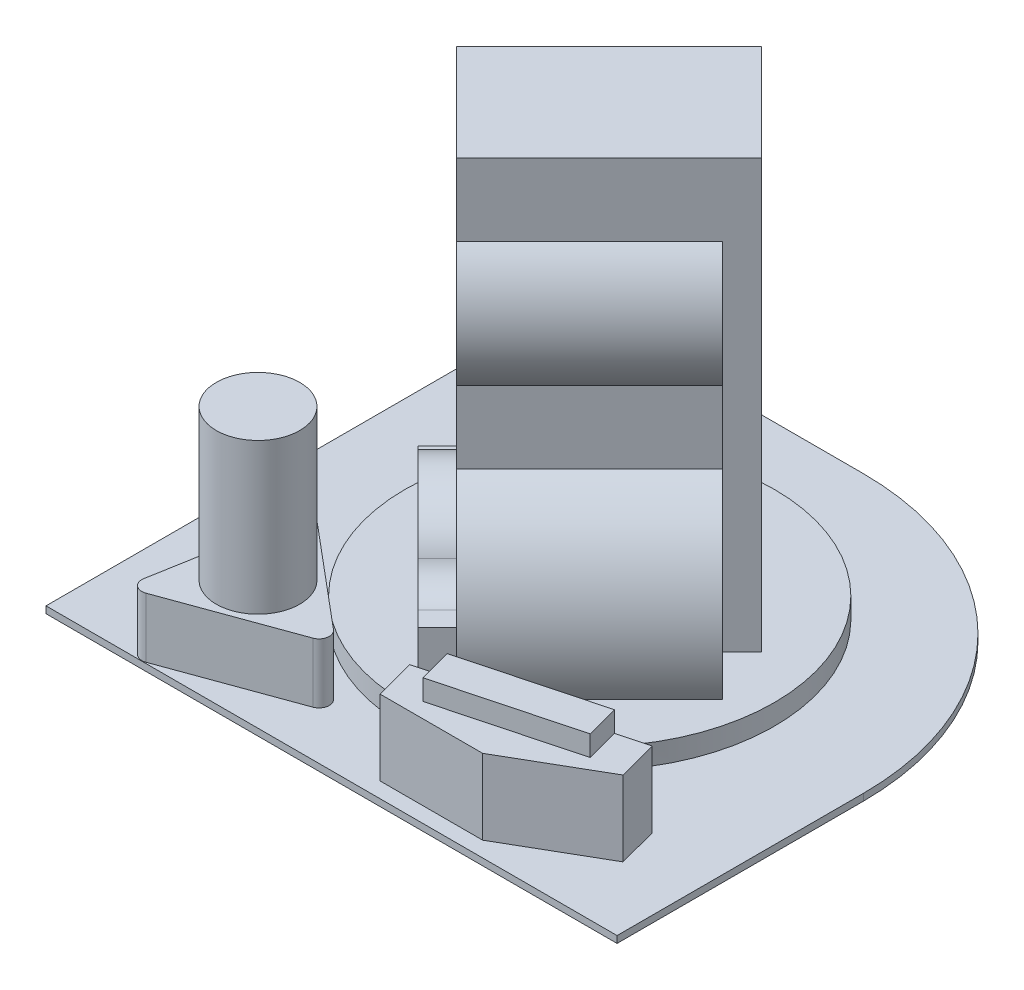
SolidWorks part; units mm, degrees
ref_plane "Front Plane" through (0, 0, 0) normal (0, 0, 1) x (1, 0, 0)
ref_plane "Top Plane" through (0, 0, 0) normal (0, 1, 0) x (1, 0, 0)
ref_plane "Right Plane" through (0, 0, 0) normal (1, 0, 0) x (0, 0, -1)
sketch "Sketch2" plane through (0, 0, 0) normal (0, 1, 0) x (1, 0, 0)
  line L1 (-83.5, -76.5) -> (83.5, -76.5)
  line L2 (-83.5, -76.5) -> (-83.5, 76.5)
  line L3 (-83.5, 76.5) -> (2.5, 76.5)
  line L4 (83.5, -76.5) -> (83.5, -4.5)
  line L5 (-83.5, -76.5) -> (83.5, 76.5) construction
  line L6 (-83.5, 76.5) -> (83.5, -76.5) construction
  arc A0 (2.5, 76.5) -> (83.5, -4.5) centre (2.5, -4.5) cw
  point P0 (0, 0)
  dimension "D3" = 81
  dimension "D1" = 153
  dimension "D2" = 167
extrude "Boss-Extrude1" add sketch "Sketch2" along normal blind 2
sketch "Sketch3" plane through (0, 2, 0) normal (0, 1, 0) x (1, 0, 0)
  line L0 (-83.5, 76.5) -> (-83.5, -76.5) construction
  line L1 (-83.5, -76.5) -> (83.5, -76.5) construction
  circle A0 centre (-0.5, -0.5) radius 54
  dimension "D1" = 83
  dimension "D2" = 76
  dimension "D3" = 108
extrude "Cut-Extrude1" cut sketch "Sketch3" against normal blind 2
ref_plane "Plane1" through (-0.5, 0, 0) normal (1, 0, 0) x (0, 0, -1)
sketch "Sketch9" plane through (-0.5, 0, 0) normal (1, 0, 0) x (0, 0, -1)
  line L0 (-0.5, 2) -> (-0.5, 23.2913) construction
ref_plane "tire_angle_plane" through (-0.5, 0, 0.5) normal (0.7071, 0, -0.7071) x (0, 1, 0)
sketch "Sketch4" plane through (-0.8536, 0, 0.1464) normal (0.7071, 0, -0.7071) x (-0.7071, 0, -0.7071)
  line L0 (-62.7254, 0) -> (51.8259, 0) construction
  circle A0 centre (-0.5, 23) radius 40
  dimension "D1" = 80
  dimension "D2" = 23
extrude "tire" add sketch "Sketch4" along normal mid plane 55
sketch "Sketch5" plane through (0, 2, 0) normal (0, 1, 0) x (1, 0, 0)
  line L0 (-83.5, 76.5) -> (-83.5, -76.5) construction
  line L1 (-17.9059, -58.0221) -> (-47.0961, -33.5286)
  line L2 (-51.9789, -35.3058) -> (-58.5958, -72.832)
  line L3 (-54.6153, -76.1721) -> (-18.8082, -63.1393)
  line L4 (-83.5, -76.5) -> (83.5, -76.5) construction
  circle A0 centre (-41.5, -56.5) radius 14 construction
  arc A1 (-17.9059, -58.0221) -> (-18.8082, -63.1393) centre (-19.8342, -60.3203) cw
  arc A2 (-58.5958, -72.832) -> (-54.6153, -76.1721) centre (-55.6413, -73.353) ccw
  arc A3 (-47.0961, -33.5286) -> (-51.9789, -35.3058) centre (-49.0244, -35.8268) ccw
  dimension "D4" = 3
  dimension "D1" = 42
  dimension "D2" = 20
  dimension "D3" = 14
  dimension "D5" = 20
extrude "steer_gear" add sketch "Sketch5" along normal blind 17.5
sketch "Sketch6" plane through (0, 19.5, 0) normal (0, 1, 0) x (1, 0, 0)
  line L0 (-54.6153, -76.1721) -> (-18.8082, -63.1393) construction
  line L1 (-51.9789, -35.3058) -> (-58.5958, -72.832) construction
  circle A0 centre (-41.5, -56.5) radius 12.2
  dimension "D1" = 24.4
  dimension "D2" = 14
  dimension "D3" = 14
extrude "m" add sketch "Sketch6" along normal blind 44
sketch "Sketch7" plane through (0, 2, 0) normal (0, 1, 0) x (1, 0, 0)
  line L0 (6.5766, -60.2271) -> (9.6948, -72)
  line L1 (9.6948, -72) -> (39.6948, -72)
  line L2 (39.6948, -72) -> (65.7157, -56.9768)
  line L3 (65.7157, -56.9768) -> (62.6432, -45.3768)
  line L4 (62.6432, -45.3768) -> (6.5766, -60.2271)
  line L5 (39.6948, -72) -> (34.6099, -52.802) construction
  line L6 (-83.5, -76.5) -> (83.5, -76.5) construction
  circle A0 centre (-41.5, -56.5) radius 12.2 construction
  dimension "D5" = 81.1948
  dimension "D1" = 30
  dimension "D2" = 4.5
  dimension "D3" = 58
  dimension "D4" = 150
  dimension "D6" = 12
extrude "sensor_gear" add sketch "Sketch7" along normal blind 22
sketch "Sketch8" plane through (0, 24, 0) normal (0, 1, 0) x (1, 0, 0)
  line L0 (15.2766, -57.9227) -> (17.8369, -67.5894)
  line L1 (62.6432, -45.3768) -> (6.5766, -60.2271) construction
  line L2 (17.8369, -67.5894) -> (56.5036, -57.3479)
  line L3 (56.5036, -57.3479) -> (53.9432, -47.6812)
  line L4 (53.9432, -47.6812) -> (15.2766, -57.9227)
  line L5 (39.6948, -72) -> (34.6099, -52.802) construction
  line L6 (62.6432, -45.3768) -> (6.5766, -60.2271) construction
  dimension "D1" = 10
  dimension "D2" = 40
extrude "enc" add sketch "Sketch8" along normal blind 6
sketch "Sketch10" plane through (0, 0, 0) normal (0, 1, 0) x (1, 0, 0)
  circle A0 centre (-0.5, -0.5) radius 54 construction
  circle A1 centre (-0.5, -0.5) radius 54
extrude "Boss-Extrude7" add sketch "Sketch10" along normal blind 8
sketch "Sketch11" plane through (-0.5, 0, 0.5) normal (0.7071, 0, -0.7071) x (0, 1, 0)
  line L0 (56.0537, 22.5267) -> (77.2266, 22.5267)
  line L1 (77.2266, 22.5267) -> (87.5203, 29.7344) construction
  line L2 (23, 0) -> (93, 0) construction
  line L3 (56.0537, -22.5267) -> (77.2266, -22.5267)
  circle A0 centre (93, 0) radius 27.5
  arc A1 (8, -37.081) -> (8, 37.081) centre (23, 0) ccw construction
  arc A2 (8, -37.081) -> (8, 37.081) centre (23, 0) ccw construction
  arc A3 (56.0537, 22.5267) -> (56.0537, -22.5267) centre (23, 0) cw
  dimension "D1" = 55
  dimension "D2" = 145
  dimension "D3" = 70
extrude "Boss-Extrude8" add sketch "Sketch11" along normal mid plane 55 contours A0 | L0 A3 L3 A0
sketch "Sketch12" plane through (-0.5, 0, 0.5) normal (0.7071, 0, -0.7071) x (0, 1, 0)
  line L0 (133, 20) -> (8, 20)
  line L1 (133, 20) -> (133, -20)
  line L2 (8, 20) -> (8, -20)
  line L3 (133, -20) -> (8, -20)
  line L4 (133, 20) -> (8, -20) construction
  line L5 (8, 20) -> (133, -20) construction
  line L6 (8, -54) -> (8, 54) construction
  arc A0 (77.2266, -22.5267) -> (77.2266, 22.5267) centre (93, 0) ccw construction
  point P0 (8, 29)
  point P1 (70.5, 0)
  dimension "D1" = 40
  dimension "D2" = 40
extrude "Boss-Extrude9" add sketch "Sketch12" along normal blind 8 from surface at 27.5 starting at face at (18.9454, 55.1617, -18.9454)
sketch "Sketch14" plane through (-19.9454, 0, 19.9454) normal (-0.7071, 0, 0.7071) x (0.7071, 0, 0.7071)
  line L0 (-37.081, 8) -> (37.081, 8) construction
  line L1 (-32.5, 8) -> (32.5, 8)
  line L2 (-32.5, 8) -> (-32.5, 23)
  line L3 (-32.5, 23) -> (-26.1534, 23)
  line L4 (32.5, 8) -> (32.5, 23)
  line L6 (0, 23) -> (0, 8) construction
  line L7 (26.1534, 23) -> (32.5, 23)
  arc A0 (16.8129, 29.4286) -> (-16.8129, 29.4286) centre (0, 23) ccw
  arc A1 (-26.1534, 23) -> (-16.8129, 29.4286) centre (-26.1534, 33) ccw
  arc A2 (16.8129, 29.4286) -> (26.1534, 23) centre (26.1534, 33) ccw
  point P9 (0, 9.0446)
  point P11 (11.3956, 19.2397)
  point P18 (-20.1897, 21.7393)
  dimension "D1" = 36
  dimension "D2" = 10
  dimension "D3" = 10
  dimension "D4" = 65
extrude "Boss-Extrude10" add sketch "Sketch14" along normal blind 8
sketch "Sketch15" plane through (18.9454, 0, -18.9454) normal (-0.7071, 0, 0.7071) x (0.7071, 0, 0.7071)
  line L9 (-20, 133) -> (-20, 111.8746)
  line L10 (20, 133) -> (-20, 133)
  line L11 (20, 111.8746) -> (20, 133)
  line L12 (-20, 133) -> (-20, 111.8746)
  line L13 (20, 133) -> (-20, 133)
  line L14 (20, 111.8746) -> (20, 133)
  arc A3 (20, 111.8746) -> (-20, 111.8746) centre (0, 93) ccw
  arc A4 (20, 111.8746) -> (-20, 111.8746) centre (0, 93) ccw
  dimension "D1" = 0
extrude "Boss-Extrude11" add sketch "Sketch15" along normal up to surface (55 mm away) up to face at (-19.9454, 36.1782, 19.9454)
